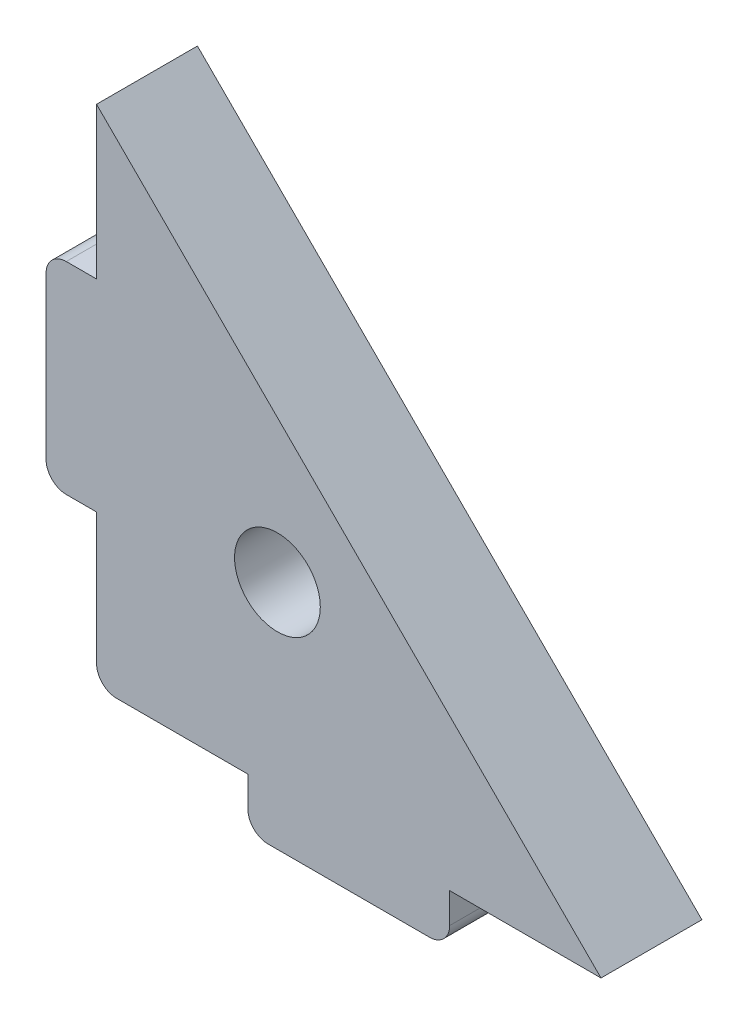
SolidWorks part; units mm, degrees
ref_plane "Front Plane" through (0, 0, 0) normal (0, 0, 1) x (1, 0, 0)
ref_plane "Top Plane" through (0, 0, 0) normal (0, 1, 0) x (1, 0, 0)
ref_plane "Right Plane" through (0, 0, 0) normal (1, 0, 0) x (0, 0, -1)
sketch "Sketch1" plane through (0, 0, 0) normal (0, 0, 1) x (1, 0, 0)
  line L1 (48.253, 14.5393) -> (-1.747, 64.5393)
  line L3 (23.253, 14.5393) -> (-1.747, 39.5393) construction
  line L4 (-1.747, 14.5393) -> (23.253, 39.5393) construction
  line L9 (-1.747, 14.5393) -> (13.253, 14.5393)
  line L15 (13.253, 14.5393) -> (13.253, 9.5393)
  line L16 (13.253, 9.5393) -> (33.253, 9.5393)
  line L17 (33.253, 14.5393) -> (33.253, 9.5393)
  line L18 (33.253, 14.5393) -> (48.253, 14.5393)
  line L19 (-1.747, 29.5393) -> (-6.747, 29.5393)
  line L20 (-6.747, 29.5393) -> (-6.747, 49.5393)
  line L21 (-1.747, 49.5393) -> (-6.747, 49.5393)
  line L22 (-1.747, 14.5393) -> (-1.747, 29.5393)
  line L23 (-1.747, 64.5393) -> (-1.747, 49.5393)
  circle A0 centre (16.1819, 32.4683) radius 4.25
  point P4 (23.253, 7.9798)
  dimension "D2" = 50
  dimension "D1" = 8.5
  dimension "D3" = 10
  dimension "D4" = 25
  dimension "D5" = 20
  dimension "D6" = 5
  dimension "D7" = 15
extrude "Boss-Extrude1" add sketch "Sketch1" along normal blind 10 contours L9 L15 L16 L17 L18 L1 L23 L21 L20 L19 L22 | A0
fillet "Fillet1" radius 2 5 edges at (33.253, 9.5393, 5) (13.253, 9.5393, 5) (-6.747, 49.5393, 5) (-6.747, 29.5393, 5) (-1.747, 14.5393, 5)
ref_plane "Plane1" through (-8.1432, 8.1432, 0) normal (0.7071, -0.7071, 0) x (0, 0, -1)
sketch "Sketch2" plane through (-1.747, 0, 0) normal (-1, 0, 0) x (0, 0, 1)
  line L0 (0, 49.5393) -> (10, 29.5393) construction
  line L5 (10, 49.5393) -> (0, 29.5393) construction
  line L7 (0, 29.4393) -> (10, 29.4393)
  line L8 (0, 29.4393) -> (0, 49.6393)
  line L9 (0, 49.6393) -> (10, 49.6393)
  line L10 (10, 29.4393) -> (10, 49.6393)
  line L11 (0, 29.4393) -> (10, 49.6393) construction
  line L12 (0, 49.6393) -> (10, 29.4393) construction
  point P8 (5, 39.5393)
  point P9 (5, 39.5393)
  dimension "D1" = 20.2
  dimension "D2" = 10
sketch "Sketch4" plane through (0, 14.5393, 0) normal (0, -1, 0) x (1, 0, 0)
  line L0 (13.253, 10) -> (33.253, 0) construction
  line L1 (30.25, 0) -> (-30.25, 0) construction
  line L2 (33.253, 10) -> (33.253, 0) construction
  line L3 (33.253, 10) -> (13.253, 0) construction
  line L5 (13.153, 0) -> (33.353, 0)
  line L6 (13.153, 0) -> (13.153, 10)
  line L7 (13.153, 10) -> (33.353, 10)
  line L8 (33.353, 0) -> (33.353, 10)
  line L9 (13.153, 0) -> (33.353, 10) construction
  line L10 (13.153, 10) -> (33.353, 0) construction
  point P10 (23.253, 5)
  point P11 (23.253, 5)
  dimension "D1" = 10
  dimension "D2" = 20.2
